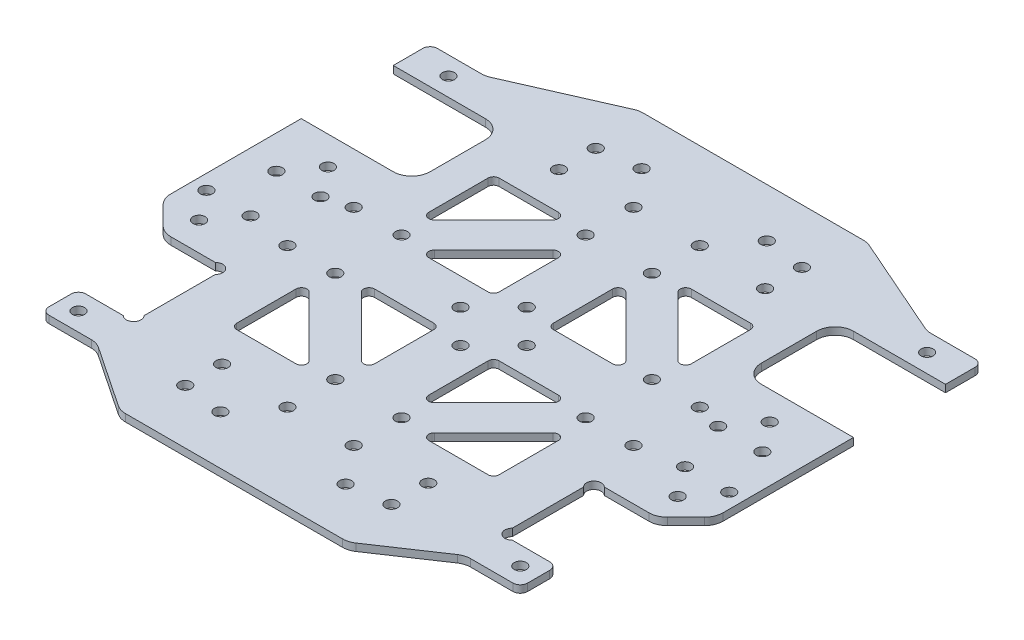
SolidWorks part; units mm, degrees
ref_plane "前视基准面" through (0, 0, 0) normal (0, 0, 1) x (1, 0, 0)
ref_plane "上视基准面" through (0, 0, 0) normal (0, 1, 0) x (1, 0, 0)
ref_plane "右视基准面" through (0, 0, 0) normal (1, 0, 0) x (0, 0, -1)
sketch "草图1" plane through (0, 0, 0) normal (0, 1, 0) x (1, 0, 0)
  line L1 (-75, -70.5) -> (75, -70.5)
  line L2 (-75, -70.5) -> (-75, 70.5)
  line L3 (-75, 70.5) -> (75, 70.5)
  line L4 (75, -70.5) -> (75, 70.5)
  line L5 (-75, -70.5) -> (75, 70.5) construction
  line L6 (-75, 70.5) -> (75, -70.5) construction
  point P0 (0, 0)
  dimension "D1" = 141
  dimension "D2" = 150
extrude "凸台-拉伸1" add sketch "草图1" along normal blind 2
sketch "草图2" plane through (0, 2, 0) normal (0, 1, 0) x (1, 0, 0)
  line L0 (-60, -11) -> (-65, -11) construction
  line L1 (-60, -11) -> (60, -11) construction
  line L2 (-60, -11) -> (-60, 11) construction
  line L3 (-60, 11) -> (60, 11) construction
  line L4 (60, -11) -> (60, 11) construction
  line L5 (-60, -11) -> (60, 11) construction
  line L6 (-60, 11) -> (60, -11) construction
  line L11 (-75, 70.5) -> (-75, -70.5) construction
  line L12 (-66, 7) -> (-54, 7) construction
  line L13 (-71, -15) -> (-59, -15) construction
  line L14 (-66, 7) -> (-66, 15) construction
  line L15 (-66, 15) -> (-54, 15) construction
  line L16 (-54, 7) -> (-54, 15) construction
  line L17 (-66, 7) -> (-54, 15) construction
  line L18 (-66, 15) -> (-54, 7) construction
  line L19 (-71, -15) -> (-71, -7) construction
  line L20 (-71, -7) -> (-59, -7) construction
  line L21 (-59, -15) -> (-59, -7) construction
  line L22 (-71, -15) -> (-59, -7) construction
  line L23 (-71, -7) -> (-59, -15) construction
  circle A4 centre (-60, 15) radius 1.65
  circle A5 centre (-66, 7) radius 1.65
  circle A6 centre (-54, 7) radius 1.65
  circle A7 centre (-71, -7) radius 1.65
  circle A8 centre (-59, -7) radius 1.65
  circle A9 centre (-65, -15) radius 1.65
  point P0 (0, 0)
  point P14 (-60, 0)
  dimension "D5" = 3.3
  dimension "D1" = 12
  dimension "D2" = 8
  dimension "D3" = 15
  dimension "D4" = 15
  dimension "D6" = 5
  dimension "D7" = 8
  dimension "D8" = 12
extrude "切除-拉伸1" cut sketch "草图2" against normal up to next
sketch "草图9" plane through (0, 2, 0) normal (0, 1, 0) x (1, 0, 0)
  line L0 (0, 22.75) -> (0, -22.75) construction
  line L1 (-75, -70.5) -> (-50, -70.5)
  line L2 (-75, -70.5) -> (-75, -22.75)
  line L3 (-75, -22.75) -> (-50, -22.75)
  line L4 (-50, -70.5) -> (-50, -22.75)
  line L5 (75, -70.5) -> (50, -70.5)
  line L6 (75, -70.5) -> (75, -22.75)
  line L7 (75, -22.75) -> (50, -22.75)
  line L8 (50, -70.5) -> (50, -22.75)
  point P14 (0, 0)
  dimension "D1" = 45.5
  dimension "D2" = 100
extrude "切除-拉伸5" cut sketch "草图9" against normal up to next
sketch "草图10" plane through (0, 2, 0) normal (0, 1, 0) x (1, 0, 0)
  line L0 (-75, 70.5) -> (-31, 70.5)
  line L1 (75, 70.5) -> (-75, 70.5) construction
  line L2 (-31, 70.5) -> (-60, 57.75)
  line L3 (-60, 57.75) -> (-75, 57.75)
  line L4 (-75, 70.5) -> (-75, -22.75) construction
  line L5 (-75, 57.75) -> (-75, 70.5)
  line L6 (0, 70.5) -> (-31, 70.5) construction
  dimension "D1" = 15
  dimension "D2" = 12.75
  dimension "D3" = 31
extrude "切除-拉伸6" cut sketch "草图10" against normal up to next
mirror "镜向1" about plane through (0, 0, 0) normal (1, 0, 0) of "切除-拉伸6", "切除-拉伸1"
chamfer "倒角1" distance 8 angle 45 2 edges at (75, 1, 22.75) (-75, 1, 22.75)
sketch "草图11" plane through (0, 2, 0) normal (0, 1, 0) x (1, 0, 0)
  line L0 (-75, 57.75) -> (-75, -14.75) construction
  line L1 (-75, 47.75) -> (-45, 47.75)
  line L2 (-75, 47.75) -> (-75, 22.75)
  line L3 (-75, 22.75) -> (-45, 22.75)
  line L4 (-45, 47.75) -> (-45, 22.75)
  line L5 (-75, 57.75) -> (-60, 57.75) construction
  line L6 (0, 0) -> (0, 70.5) construction
  line L7 (31, 70.5) -> (-31, 70.5) construction
  line L8 (75, 22.75) -> (45, 22.75)
  line L9 (45, 47.75) -> (45, 22.75)
  line L10 (75, 47.75) -> (45, 47.75)
  line L11 (75, 47.75) -> (75, 22.75)
  dimension "D1" = 10
  dimension "D2" = 30
  dimension "D3" = 25
extrude "切除-拉伸7" cut sketch "草图11" against normal up to next
sketch "草图12" plane through (0, 2, 0) normal (0, 1, 0) x (1, 0, 0)
  line L0 (-75, 52.75) -> (-65, 52.75) construction
  line L1 (-75, 57.75) -> (-75, 47.75) construction
  line L2 (0, 0) -> (0, 70.5) construction
  line L3 (31, 70.5) -> (-31, 70.5) construction
  circle A0 centre (-65, 52.75) radius 1.65
  circle A1 centre (65, 52.75) radius 1.65
  dimension "D1" = 3.3
  dimension "D2" = 10
extrude "切除-拉伸8" cut sketch "草图12" against normal up to next
fillet "圆角1" radius 5 8 edges at (75, 1, 14.75) (67, 1, 22.75) (-67, 1, 22.75) (-75, 1, 14.75) (45, 1, -22.75) (45, 1, -47.75) (-45, 1, -22.75) (-45, 1, -47.75)
sketch "草图13" plane through (0, 2, 0) normal (0, 1, 0) x (1, 0, 0)
  line L0 (-50, -70.5) -> (-50, -57.75)
  line L1 (-50, -70.5) -> (-50, -22.75) construction
  line L2 (-50, -57.75) -> (-31, -70.5)
  line L3 (-50, -70.5) -> (50, -70.5) construction
  line L4 (-31, -70.5) -> (-50, -70.5)
  line L5 (31, -70.5) -> (-31, -70.5) construction
  point P11 (0, -70.5)
  dimension "D1" = 12.75
  dimension "D2" = 62
extrude "切除-拉伸9" cut sketch "草图13" against normal up to next
sketch "草图14" plane through (0, 0, 0) normal (0, 1, 0) x (1, 0, 0)
  line L1 (-50, -57.75) -> (-65, -57.75)
  line L2 (-50, -57.75) -> (-50, -47.75)
  line L3 (-50, -47.75) -> (-65, -47.75)
  line L4 (-65, -57.75) -> (-65, -47.75)
  dimension "D1" = 15
  dimension "D2" = 10
extrude "凸台-拉伸2" add sketch "草图14" along normal up to surface (2 mm away) up to face at (-65, 2, -51.1)
sketch "草图15" plane through (0, 2, 0) normal (0, 1, 0) x (1, 0, 0)
  line L0 (-65, -52.75) -> (-60, -52.75) construction
  line L1 (-65, -57.75) -> (-65, -47.75) construction
  circle A0 centre (-60, -52.75) radius 1.65
  dimension "D2" = 3.3
  dimension "D1" = 5
extrude "切除-拉伸10" cut sketch "草图15" against normal up to next
sketch "草图18" plane through (0, 2, 0) normal (0, 1, 0) x (1, 0, 0)
  line L0 (-51.4142, -46.3358) -> (-50, -47.75) construction
  line L1 (-51.4142, -24.1642) -> (-50, -22.75) construction
  line L2 (-50, -47.75) -> (-50, -22.75) construction
  circle A0 centre (-51.4142, -24.1642) radius 2
  circle A1 centre (-51.4142, -46.3358) radius 2
  dimension "10" = 4
  dimension "D1" = 45
  dimension "D2" = 45
extrude "切除-拉伸13" cut sketch "草图18" against normal up to next
sketch "草图19" plane through (0, 2, 0) normal (0, 1, 0) x (1, 0, 0)
  line L0 (0, 0) -> (-34, 0) construction
  line L1 (-34, 0) -> (-47, 0) construction
  line L2 (-47, 9) -> (-47, -9) construction
  line L3 (-34, 9) -> (-34, -9) construction
  line L4 (-47, -9) -> (-34, -9) construction
  circle A0 centre (-47, 9) radius 1.65
  circle A1 centre (-47, -9) radius 1.65
  circle A2 centre (-34, -9) radius 1.65
  circle A3 centre (-34, 9) radius 1.65
  point P6 (-47, 0)
  point P10 (-34, 0)
  dimension "D2" = 3.3
  dimension "D1" = 18
  dimension "D3" = 47
  dimension "D4" = 13
extrude "切除-拉伸14" cut sketch "草图19" against normal up to next
mirror "镜向2" about plane through (0, 0, 0) normal (1, 0, 0) of "切除-拉伸13", "切除-拉伸10", "切除-拉伸9", "凸台-拉伸2"
mirror "镜向4" about plane through (0, 0, 0) normal (1, 0, 0) of "切除-拉伸14"
sketch "草图20" plane through (0, 2, 0) normal (0, 1, 0) x (1, 0, 0)
  line L0 (0, 9) -> (0, -9) construction
  circle A0 centre (0, 9) radius 1.65
  circle A1 centre (0, -9) radius 1.65
  point P4 (0, 0)
  dimension "D2" = 3.3
  dimension "D1" = 18
extrude "切除-拉伸15" cut sketch "草图20" against normal up to next
fillet "圆角2" radius 2 6 edges at (75, 1, -57.75) (-75, 1, -57.75) (65, 1, 57.75) (65, 1, 47.75) (-65, 1, 57.75) (-65, 1, 47.75)
sketch "草图17" plane through (0, 2, 0) normal (0, 1, 0) x (1, 0, 0)
  line L0 (0, 0) -> (0, -50.75) construction
  line L2 (-28, -55.75) -> (28, -55.75) construction
  line L3 (-28, -55.75) -> (-28, -45.75) construction
  line L4 (-28, -45.75) -> (28, -45.75) construction
  line L5 (28, -55.75) -> (28, -45.75) construction
  line L6 (-28, -55.75) -> (28, -45.75) construction
  line L7 (-28, -45.75) -> (28, -55.75) construction
  circle A0 centre (-28, -45.75) radius 1.65
  circle A1 centre (-28, -55.75) radius 1.65
  circle A2 centre (28, -45.75) radius 1.65
  circle A3 centre (28, -55.75) radius 1.65
  dimension "D4" = 3.3
  dimension "D1" = 50.75
  dimension "D2" = 10
  dimension "D3" = 56
extrude "切除-拉伸12" cut sketch "草图17" against normal up to next
mirror "镜向3" about plane through (0, 0, 0) normal (0, 0, 1) of "切除-拉伸12"
fillet "圆角3" radius 5 8 edges at (50, 1, 57.75) (31, 1, 70.5) (-31, 1, 70.5) (-50, 1, 57.75) (60, 1, -57.75) (31, 1, -70.5) (-31, 1, -70.5) (-60, 1, -57.75)
sketch "草图21" plane through (0, 0, 0) normal (0, 0, 1) x (1, 0, 0)
  line L0 (0, 0) -> (0, 2) construction
  line L1 (-29.4778, 2) -> (29.4778, 2) construction
pattern_circular "阵列(圆周)1" count 2 every 90 about axis through (0, 0, 0) along (0, 1, 0) of "镜向4", "切除-拉伸15", "切除-拉伸14"
sketch "草图22" [suppressed] plane through (0, 2, 0) normal (0, 1, 0) x (1, 0, 0)
  line L0 (-40, -26.2855) -> (-40, -47.75)
  line L1 (-40, -47.75) -> (-8.1802, -15.9302)
  line L2 (-8.1802, -15.9302) -> (-18.9124, -5.198)
  line L3 (-18.9124, -5.198) -> (-40, -26.2855)
  line L4 (-50, -44.2145) -> (-50, -26.2855) construction
  line L5 (-63, -47.75) -> (-53.5355, -47.75) construction
  line L6 (-50, -26.2855) -> (-40, -26.2855) construction
  dimension "D1" = 45
  dimension "D2" = 10
  dimension "D3" = 45
sketch "草图23" plane through (0, 2, 0) normal (0, 1, 0) x (1, 0, 0)
  line L0 (-50, -47.75) -> (-50, -22.75) construction
  line L1 (-50, -22.75) -> (-47, -9) construction
  line L2 (-47, -9) -> (-34, -9) construction
  line L3 (-34, -9) -> (-9, 0) construction
  line L4 (-9, 0) -> (0, -9) construction
  line L5 (0, -9) -> (-9, -34) construction
  line L6 (-9, -34) -> (-28, -45.75) construction
  line L7 (-28, -45.75) -> (-50, -47.75) construction
  line L8 (-30.2778, -38.9282) -> (-43, -40.0848)
  line L9 (-43, -40.0848) -> (-43, -23.5048)
  line L10 (-43, -23.5048) -> (-41.3626, -16)
  line L11 (-41.3626, -16) -> (-32.7784, -16)
  line L12 (-32.7784, -16) -> (-10.8086, -8.0909)
  line L13 (-10.8086, -8.0909) -> (-8.0909, -10.8086)
  line L14 (-8.0909, -10.8086) -> (-14.759, -29.331)
  line L15 (-14.759, -29.331) -> (-30.2778, -38.9282)
  line L16 (-28, 45.75) -> (-9, 34) construction
  line L17 (-9, 34) -> (0, 9) construction
  line L18 (0, 9) -> (-9, 0) construction
  line L19 (-9, 0) -> (-34, 9) construction
  line L20 (-34, 9) -> (-47, 9) construction
  line L21 (-47, 9) -> (-45, 27.75) construction
  line L22 (-45, 27.75) -> (-45, 42.75) construction
  line L23 (-45, 42.75) -> (-28, 45.75) construction
  line L24 (-38, 36.8771) -> (-29.4118, 38.3927)
  line L25 (-29.4118, 38.3927) -> (-14.759, 29.331)
  line L26 (-14.759, 29.331) -> (-8.0909, 10.8086)
  line L27 (-8.0909, 10.8086) -> (-10.8086, 8.0909)
  line L28 (-10.8086, 8.0909) -> (-32.7784, 16)
  line L29 (-32.7784, 16) -> (-39.2136, 16)
  line L30 (-39.2136, 16) -> (-38, 27.3777)
  line L31 (-38, 27.3777) -> (-38, 36.8771)
  arc A0 (-52.8284, -47.75) -> (-50, -44.9216) centre (-51.4142, -46.3358) ccw construction
  arc A1 (-50, -25.5784) -> (-52.8284, -22.75) centre (-51.4142, -24.1642) ccw construction
  arc A2 (-50, 22.75) -> (-45, 27.75) centre (-50, 27.75) ccw construction
  dimension "D1" = 7
  dimension "D2" = 7
extrude "切除-拉伸16" [suppressed] cut sketch "草图23" against normal up to next
mirror "镜向5" [suppressed] about plane through (0, 0, 0) normal (1, 0, 0)
sketch "草图24" plane through (0, 2, 0) normal (0, 1, 0) x (1, 0, 0)
  line L4 (0, 0) -> (-39.2798, 39.2798) construction
  line L5 (-46.5276, 32.0319) -> (-32.0319, 46.5276) construction
  line L6 (-75, 22.75) -> (-50, 22.75) construction
  circle A0 centre (-46.5276, 32.0319) radius 1.25
  circle A1 centre (-32.0319, 46.5276) radius 1.25
  point P5 (-39.2798, 39.2798)
  dimension "D4" = 2.5
  dimension "D1" = 20.5
  dimension "D2" = 55.55
  dimension "D3" = 45
extrude "切除-拉伸17" [suppressed] cut sketch "草图24" against normal up to next
pattern_circular "阵列(圆周)2" [suppressed] count 4 over 360 about axis through (0, 0, 0) along (0, 1, 0)
sketch "草图25" plane through (0, 2, 0) normal (0, 1, 0) x (1, 0, 0)
  line L1 (-17, -57.2) -> (17, -57.2) construction
  line L2 (-17, -57.2) -> (-17, 57.2) construction
  line L3 (-17, 57.2) -> (17, 57.2) construction
  line L4 (17, -57.2) -> (17, 57.2) construction
  line L5 (-17, -57.2) -> (17, 57.2) construction
  line L6 (-17, 57.2) -> (17, -57.2) construction
  circle A0 centre (17, 57.2) radius 1.65
  circle A1 centre (-17, 57.2) radius 1.65
  circle A2 centre (-17, -57.2) radius 1.65
  circle A3 centre (17, -57.2) radius 1.65
  point P0 (0, 0)
  dimension "D3" = 3.3
  dimension "D1" = 114.4
  dimension "D2" = 34
extrude "切除-拉伸18" cut sketch "草图25" against normal up to next
sketch "草图26" plane through (0, 2, 0) normal (0, 1, 0) x (1, 0, 0)
  line L0 (-28.5711, -7.3579) -> (-7.3579, -28.5711)
  line L1 (-28.5711, -7.3579) -> (-35.6421, -14.4289) construction
  line L2 (-7.3579, -28.5711) -> (-14.4289, -35.6421) construction
  line L3 (-35.6421, -14.4289) -> (-14.4289, -35.6421)
  line L4 (-10.8934, -32.1066) -> (-32.1066, -10.8934) construction
  line L5 (-17.9645, -17.9645) -> (-25.0355, -25.0355) construction
  line L6 (-75, 22.75) -> (-75, -12.6789) construction
  line L7 (-35.6421, -14.4289) -> (-35.6421, -35.6421)
  line L8 (-35.6421, -35.6421) -> (-14.4289, -35.6421)
  line L9 (-7.3579, -28.5711) -> (-7.3579, -7.3579)
  line L10 (-7.3579, -7.3579) -> (-28.5711, -7.3579)
  line L11 (14.4289, 35.6421) -> (35.6421, 14.4289)
  line L12 (14.4289, 35.6421) -> (7.3579, 28.5711) construction
  line L13 (35.6421, 14.4289) -> (28.5711, 7.3579) construction
  line L14 (7.3579, 28.5711) -> (28.5711, 7.3579)
  line L15 (32.1066, 10.8934) -> (10.8934, 32.1066) construction
  line L16 (25.0355, 25.0355) -> (17.9645, 17.9645) construction
  line L17 (7.3579, 28.5711) -> (7.3579, 7.3579)
  line L18 (7.3579, 7.3579) -> (28.5711, 7.3579)
  line L19 (35.6421, 14.4289) -> (35.6421, 35.6421)
  line L20 (35.6421, 35.6421) -> (14.4289, 35.6421)
  line L21 (75, -12.6789) -> (75, 22.75) construction
  point P1 (-21.5, -21.5)
  point P11 (21.5, 21.5)
  dimension "D1" = 45
  dimension "D2" = 10
  dimension "D3" = 30
  dimension "D4" = 21.5
  dimension "D5" = 21.5
  dimension "D6" = 10
  dimension "D7" = 30
  dimension "D8" = 21.5
  dimension "D9" = 21.5
  dimension "D10" = 45
extrude "切除-拉伸19" cut sketch "草图26" against normal up to next
fillet "圆角4" radius 1.5 12 edges at (-35.6421, 1, 14.4289) (-35.6421, 1, 35.6421) (-14.4289, 1, 35.6421) (-7.3579, 1, 28.5711) (-7.3579, 1, 7.3579) (-28.5711, 1, 7.3579) (14.4289, 1, -35.6421) (35.6421, 1, -35.6421) (35.6421, 1, -14.4289) (28.5711, 1, -7.3579) (7.3579, 1, -7.3579) (7.3579, 1, -28.5711)
mirror "镜向6" about plane through (0, 0, 0) normal (1, 0, 0) of "圆角4", "切除-拉伸19"
sketch "草图27" plane through (0, 2, 0) normal (0, 1, 0) x (1, 0, 0)
  line L0 (-12.5, -12.5) -> (-33.7132, -33.7132) construction
  line L1 (-12.5, -12.5) -> (12.5, -12.5) construction
  line L2 (-12.5, -12.5) -> (-12.5, 12.5) construction
  line L3 (-12.5, 12.5) -> (12.5, 12.5) construction
  line L4 (12.5, -12.5) -> (12.5, 12.5) construction
  line L5 (-12.5, -12.5) -> (12.5, 12.5) construction
  line L6 (-12.5, 12.5) -> (12.5, -12.5) construction
  line L9 (-8.2574, -16.7426) -> (-29.4706, -37.9558)
  line L12 (-16.7426, -8.2574) -> (-37.9558, -29.4706)
  line L15 (12.5, -12.5) -> (33.7132, -33.7132) construction
  line L18 (16.7426, -8.2574) -> (37.9558, -29.4706)
  line L19 (8.2574, -16.7426) -> (29.4706, -37.9558)
  line L20 (-12.5, 12.5) -> (-26.6421, 26.6421) construction
  line L21 (-16.7426, 8.2574) -> (-30.8848, 22.3995)
  line L22 (-8.2574, 16.7426) -> (-22.3995, 30.8848)
  line L23 (12.5, 12.5) -> (26.6421, 26.6421) construction
  line L24 (8.2574, 16.7426) -> (22.3995, 30.8848)
  line L25 (16.7426, 8.2574) -> (30.8848, 22.3995)
  arc A8 (-8.2574, -16.7426) -> (-16.7426, -8.2574) centre (-12.5, -12.5) ccw
  arc A9 (-37.9558, -29.4706) -> (-29.4706, -37.9558) centre (-33.7132, -33.7132) ccw
  arc A10 (16.7426, -8.2574) -> (8.2574, -16.7426) centre (12.5, -12.5) ccw
  arc A11 (29.4706, -37.9558) -> (37.9558, -29.4706) centre (33.7132, -33.7132) ccw
  arc A12 (-16.7426, 8.2574) -> (-8.2574, 16.7426) centre (-12.5, 12.5) ccw
  arc A13 (-22.3995, 30.8848) -> (-30.8848, 22.3995) centre (-26.6421, 26.6421) ccw
  arc A14 (8.2574, 16.7426) -> (16.7426, 8.2574) centre (12.5, 12.5) ccw
  arc A15 (30.8848, 22.3995) -> (22.3995, 30.8848) centre (26.6421, 26.6421) ccw
  point P0 (0, 0)
  point P7 (-23.1066, -23.1066)
  point P12 (23.1066, -23.1066)
  point P19 (-19.5711, 19.5711)
  point P24 (19.5711, 19.5711)
  dimension "D3" = 6
  dimension "D4" = 20
  dimension "D5" = 6
  dimension "D1" = 25
  dimension "D2" = 30
extrude "切除-拉伸20" [suppressed] cut sketch "草图27" against normal up to next
